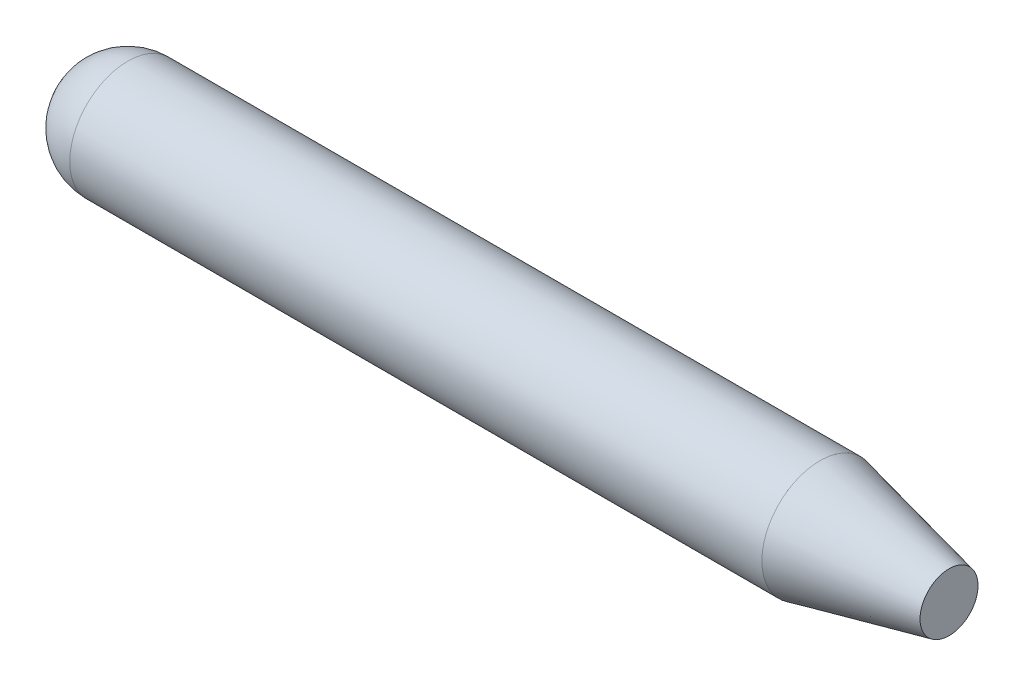
SolidWorks part; units mm, degrees
ref_plane "Front Plane" through (0, 0, 0) normal (0, 0, 1) x (1, 0, 0)
ref_plane "Top Plane" through (0, 0, 0) normal (0, 1, 0) x (1, 0, 0)
ref_plane "Right Plane" through (0, 0, 0) normal (1, 0, 0) x (0, 0, -1)
sketch "Sketch1" plane through (0, 0, 0) normal (0, 0, 1) x (1, 0, 0)
  line L0 (0, 0) -> (1040.2752, 0) construction
  line L1 (68.58, 68.58) -> (887.4078, 68.58)
  line L2 (887.4078, 68.58) -> (1040.2752, 34.3254)
  line L3 (1040.2752, 34.3254) -> (1040.2752, 0)
  line L4 (0, 0) -> (1040.2752, 0)
  arc A0 (68.58, 68.58) -> (0, 0) centre (68.58, 0) ccw
  point P4 (887.5817, 68.58)
  dimension "D1" = 68.58
revolve "Revolve1" add sketch "Sketch1" angle 360 about L0
